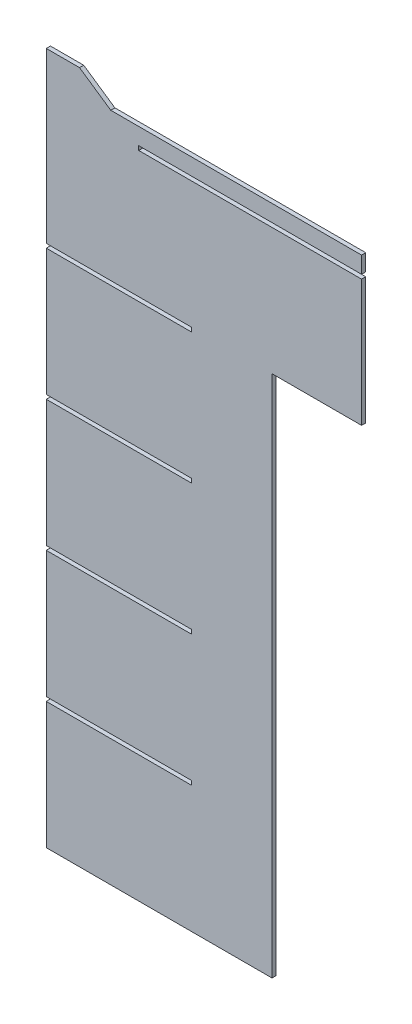
SolidWorks part; units mm, degrees
material "6061-T6 (SS)"
ref_plane "X-Y Datum" through (0, 0, 0) normal (0, 0, 1) x (1, 0, 0)
ref_plane "X-Z Datum" through (0, 0, 0) normal (0, 1, 0) x (1, 0, 0)
ref_plane "Y-Z Datum" through (0, 0, 0) normal (1, 0, 0) x (0, 0, -1)
sketch "Sketch1" plane through (0, 0, 0) normal (0, 0, 1) x (1, 0, 0)
  line L1 (129.0131, 254.2454) -> (-18.6854, 254.2454)
  line L3 (129.0131, -241.3467) -> (-18.6854, -241.3467)
  line L4 (-18.6854, 254.2454) -> (-18.6854, 157.667)
  line L24 (129.0131, 254.2454) -> (129.0131, -241.3467)
  line L25 (92.0885, 157.667) -> (-18.6854, 157.667)
  line L27 (92.0885, 154.492) -> (-18.6854, 154.492)
  line L29 (92.0885, 57.9136) -> (-18.6854, 57.9136)
  line L31 (92.0885, 54.7386) -> (-18.6854, 54.7386)
  line L33 (92.0885, -41.8399) -> (-18.6854, -41.8399)
  line L35 (92.0885, -45.0149) -> (-18.6854, -45.0149)
  line L37 (92.0885, -141.5933) -> (-18.6854, -141.5933)
  line L39 (92.0885, -144.7683) -> (-18.6854, -144.7683)
  line L41 (92.0885, -141.5933) -> (92.0885, -144.7683)
  line L42 (92.0885, -41.8399) -> (92.0885, -45.0149)
  line L43 (92.0885, 57.9136) -> (92.0885, 54.7386)
  line L44 (-18.6854, -144.7683) -> (-18.6854, -241.3467)
  line L45 (-18.6854, -45.0149) -> (-18.6854, -141.5933)
  line L46 (-18.6854, 54.7386) -> (-18.6854, -41.8399)
  line L47 (-18.6854, 154.492) -> (-18.6854, 57.9136)
  line L48 (92.0885, 157.667) -> (92.0885, 154.492)
extrude "Boss-Extrude2" add sketch "Sketch1" along normal blind 3.175
sketch "Sketch2" plane through (0, 0, 3.175) normal (0, 0, 1) x (1, 0, 0)
  line L1 (129.0131, 254.2454) -> (153.4072, 254.2454)
  line L2 (129.0131, 254.2454) -> (129.0131, -241.3467)
  line L3 (129.0131, -241.3467) -> (153.4072, -241.3467)
  line L4 (153.4072, 254.2454) -> (153.4072, -241.3467)
extrude "Boss-Extrude3" add sketch "Sketch2" against normal through all
sketch "Sketch3" plane through (0, 0, 3.175) normal (0, 0, 1) x (1, 0, 0)
  line L8 (153.4072, 6.4494) -> (-81.8872, 6.4494) construction
  line L9 (51.8072, 257.4204) -> (51.8072, 254.2454)
  line L18 (153.4072, 257.4204) -> (51.8072, 257.4204)
  line L19 (153.4072, 257.4204) -> (153.4072, 270.1204)
  line L20 (153.4072, 270.1204) -> (30.4963, 270.1204)
  line L21 (30.4963, 270.1204) -> (6.7146, 286.3764)
  line L22 (-18.6854, 286.3764) -> (6.7146, 286.3764)
  line L23 (-18.6854, 254.2454) -> (-18.6854, 286.3764)
  line L24 (51.8072, 254.2454) -> (-18.6854, 254.2454)
extrude "Boss-Extrude4" add sketch "Sketch3" against normal through all
sketch "Sketch4" plane through (0, 0, 3.175) normal (0, 0, 1) x (1, 0, 0)
  line L1 (153.4072, 270.1204) -> (221.7231, 270.1204)
  line L2 (153.4072, 270.1204) -> (153.4072, 257.4204)
  line L3 (153.4072, 257.4204) -> (221.7231, 257.4204)
  line L4 (221.7231, 270.1204) -> (221.7231, 257.4204)
  line L5 (153.4072, 254.2454) -> (221.7231, 254.2454)
  line L6 (153.4072, 254.2454) -> (153.4072, 157.667)
  line L7 (153.4072, 157.667) -> (221.7231, 157.667)
  line L8 (221.7231, 254.2454) -> (221.7231, 157.667)
  dimension "D1" = 68.3158
extrude "Boss-Extrude5" add sketch "Sketch4" against normal through all
